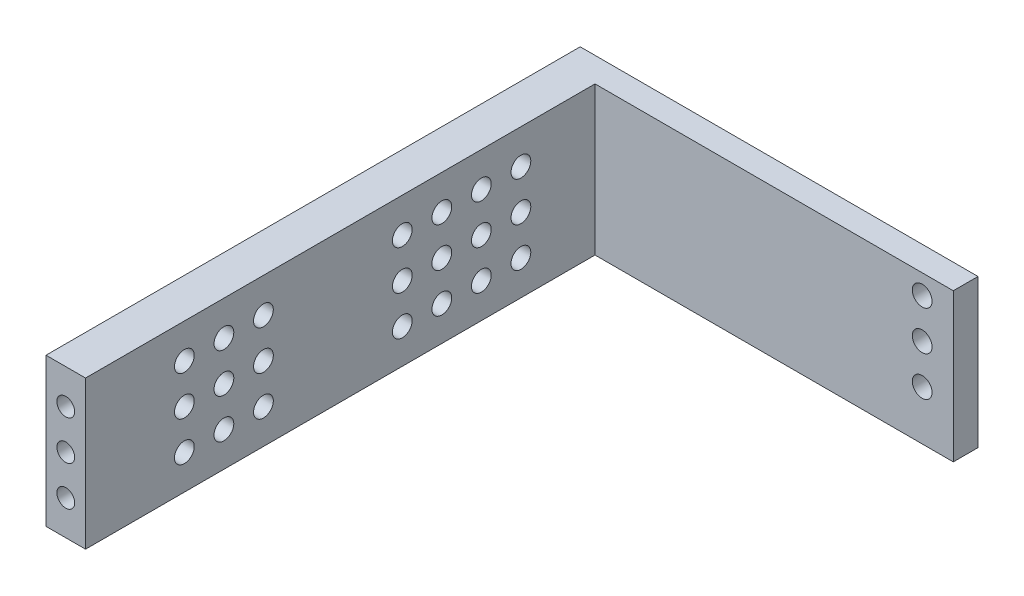
SolidWorks part; units mm, degrees
material "ABS"
ref_plane "前基準面" through (0, 0, 0) normal (0, 0, 1) x (1, 0, 0)
ref_plane "上基準面" through (0, 0, 0) normal (0, 1, 0) x (1, 0, 0)
ref_plane "右基準面" through (0, 0, 0) normal (1, 0, 0) x (0, 0, -1)
sketch "草圖1" plane through (0, 0, 0) normal (0, 1, 0) x (1, 0, 0)
  line L0 (0, 0) -> (0, 108.1)
  line L1 (0, 108.1) -> (80.5, 108.1)
  line L2 (80.5, 108.1) -> (80.5, 103.1)
  line L3 (80.5, 103.1) -> (8, 103.1)
  line L4 (8, 103.1) -> (8, 0)
  line L5 (8, 0) -> (0, 0)
  dimension "D1" = 108.1
  dimension "D2" = 80.5
  dimension "D3" = 72.5
  dimension "D4" = 5
extrude "填料-伸長1" add sketch "草圖1" along normal blind 30
sketch "草圖2" plane through (0, 0, 0) normal (0, 0, 1) x (1, 0, 0)
  line L4 (0, 30) -> (8, 30) construction
  line L6 (8, 30) -> (8, 0) construction
  circle A0 centre (4, 23) radius 1.8
  circle A1 centre (4, 7) radius 1.8
  circle A2 centre (4, 15) radius 1.8
  dimension "D1" = 8
  dimension "D3" = 7
  dimension "D4" = 4
  dimension "D5" = 3.6
  dimension "D2" = 8
sketch "草圖3" plane through (0, 0, 0) normal (-1, 0, 0) x (0, 0, 1)
  line L0 (-108.1, 30) -> (0, 30) construction
  line L2 (0, 30) -> (0, 0) construction
  line L3 (-108.1, 30) -> (-108.1, 0) construction
  circle A0 centre (-20, 23) radius 2
  circle A1 centre (-20, 15) radius 2
  circle A2 centre (-20, 7) radius 2
  circle A3 centre (-28, 23) radius 2
  circle A4 centre (-28, 15) radius 2
  circle A5 centre (-28, 7) radius 2
  circle A6 centre (-36, 23) radius 2
  circle A7 centre (-36, 15) radius 2
  circle A8 centre (-36, 7) radius 2
  circle A9 centre (-64.1, 23) radius 2
  circle A10 centre (-64.1, 15) radius 2
  circle A11 centre (-64.1, 7) radius 2
  circle A12 centre (-72.1, 23) radius 2
  circle A13 centre (-72.1, 15) radius 2
  circle A14 centre (-72.1, 7) radius 2
  circle A15 centre (-80.1, 23) radius 2
  circle A16 centre (-80.1, 15) radius 2
  circle A17 centre (-80.1, 7) radius 2
  circle A18 centre (-88.1, 23) radius 2
  circle A19 centre (-88.1, 15) radius 2
  circle A20 centre (-88.1, 7) radius 2
  dimension "D1" = 4
  dimension "D2" = 4
  dimension "D3" = 4
  dimension "D9" = 4
  dimension "D10" = 4
  dimension "D11" = 4
  dimension "D4" = 8
  dimension "D5" = 8
  dimension "D6" = 7
  dimension "D7" = 3
  dimension "D8" = 20
  dimension "D12" = 8
  dimension "D13" = 8
  dimension "D14" = 7
  dimension "D16" = 20
  dimension "D15" = 4
extrude "除料-伸長2" cut sketch "草圖3" against normal blind 10
sketch "草圖4" plane through (0, 0, -108.1) normal (0, 0, -1) x (-1, 0, 0)
  line L0 (-80.5, 30) -> (0, 30) construction
  line L1 (-80.5, 30) -> (-80.5, 0) construction
  circle A0 centre (-74.2, 26) radius 2
  circle A1 centre (-74.2, 18) radius 2
  circle A2 centre (-74.2, 10) radius 2
  dimension "D1" = 4
  dimension "D2" = 4
  dimension "D3" = 4
  dimension "D4" = 8
  dimension "D5" = 8
  dimension "D6" = 4
  dimension "D7" = 6.3
extrude "除料-伸長3" cut sketch "草圖4" against normal blind 10
extrude "除料-伸長4" cut sketch "草圖2" against normal blind 9
